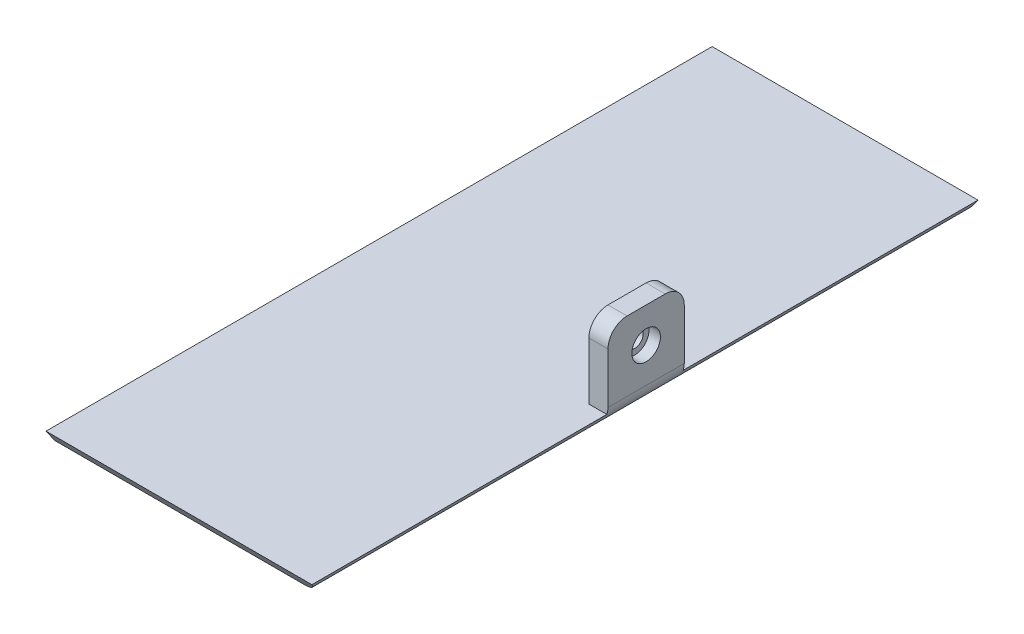
SolidWorks part; units mm, degrees
ref_plane "Front Plane" through (0, 0, 0) normal (1, 0, 0) x (0, 1, 0)
ref_plane "Top Plane" through (0, 0, 0) normal (0, 0, 1) x (0, 1, 0)
ref_plane "Right Plane" through (0, 0, 0) normal (0, 1, 0) x (-1, 0, 0)
sketch "Sketch1" plane through (0, 0, 0) normal (1, 0, 0) x (0, 1, 0)
  line L0 (-1.6383, 85) -> (1.6383, 87.2943)
  line L4 (1.6383, -87.2943) -> (1.6383, 87.2943)
  line L5 (-1.6383, -85) -> (-1.6383, 85)
  line L6 (1.6383, 0) -> (-1.6383, 0) construction
  line L7 (-1.6383, -85) -> (1.6383, -87.2943)
  point P2 (0, 0)
  point P3 (1.6383, 0)
  point P5 (-1.6383, 0)
  dimension "D1" = 55
  dimension "D2" = 4
  dimension "D3" = 85
extrude "Boss-Extrude1" add sketch "Sketch1" along normal blind 70
sketch "Sketch3" plane through (0, 1.6383, 0) normal (0, 1, 0) x (-1, 0, 0)
  line L0 (-70, -87.2943) -> (-70, 87.2943) construction
  line L1 (-65, 10) -> (-70, 10)
  line L2 (-65, 10) -> (-65, -10)
  line L3 (-65, -10) -> (-70, -10)
  line L4 (-70, 10) -> (-70, -10)
  line L5 (-65, -10) -> (-69.6936, -10) construction
  point P7 (0, 0)
  point P8 (-65, -10)
extrude "Boss-Extrude2" add sketch "Sketch3" along normal blind 20
sketch "Sketch4" plane through (0, 0, 0) normal (0, 0, 1) x (0, 1, 0)
  line L0 (-1.6383, -65) -> (-1.6383, -70)
  line L1 (-1.6383, -70) -> (3.3617, -70)
  arc A0 (-1.6383, -65) -> (3.3617, -70) centre (3.3617, -65) ccw
  arc A1 (-1.6383, -65) -> (3.3617, -70) centre (3.3617, -65) ccw construction
  point P9 (3.3617, -70)
  point P10 (0, 0)
  point P11 (0, 0)
  dimension "D1" = 10
extrude "Cut-Extrude2" cut sketch "Sketch4" against normal through all and the other way through all contours A0 L0 L1
sketch "Sketch5" plane through (70, 0, 0) normal (1, 0, 0) x (0, 1, 0)
  line L0 (21.6383, -10) -> (3.3617, -10) construction
  line L1 (3.3617, -10) -> (21.6383, -10)
  line L2 (3.3617, -10) -> (3.3617, 10)
  line L3 (3.3617, 10) -> (21.6383, 10)
  line L4 (21.6383, -10) -> (21.6383, 10)
  line L5 (3.3617, -10) -> (21.6383, 10) construction
  line L6 (3.3617, 10) -> (21.6383, -10) construction
  circle A0 centre (12.5, 0) radius 2.25
  point P0 (12.5, 0)
  dimension "D1" = 4.5
extrude "Cut-Extrude3" cut sketch "Sketch5" against normal up to next contours A0
sketch "Sketch7" plane through (70, 0, 0) normal (1, 0, 0) x (0, 1, 0)
  circle A2 centre (12.5, 0) radius 3.75
  circle A3 centre (12.5, 0) radius 3.75
  dimension "D1" = 1.5
extrude "Cut-Extrude4" cut sketch "Sketch7" against normal blind 3
fillet "Fillet1" radius 5 2 edges at (67.5, 21.6383, -10) (67.5, 21.6383, 10)
